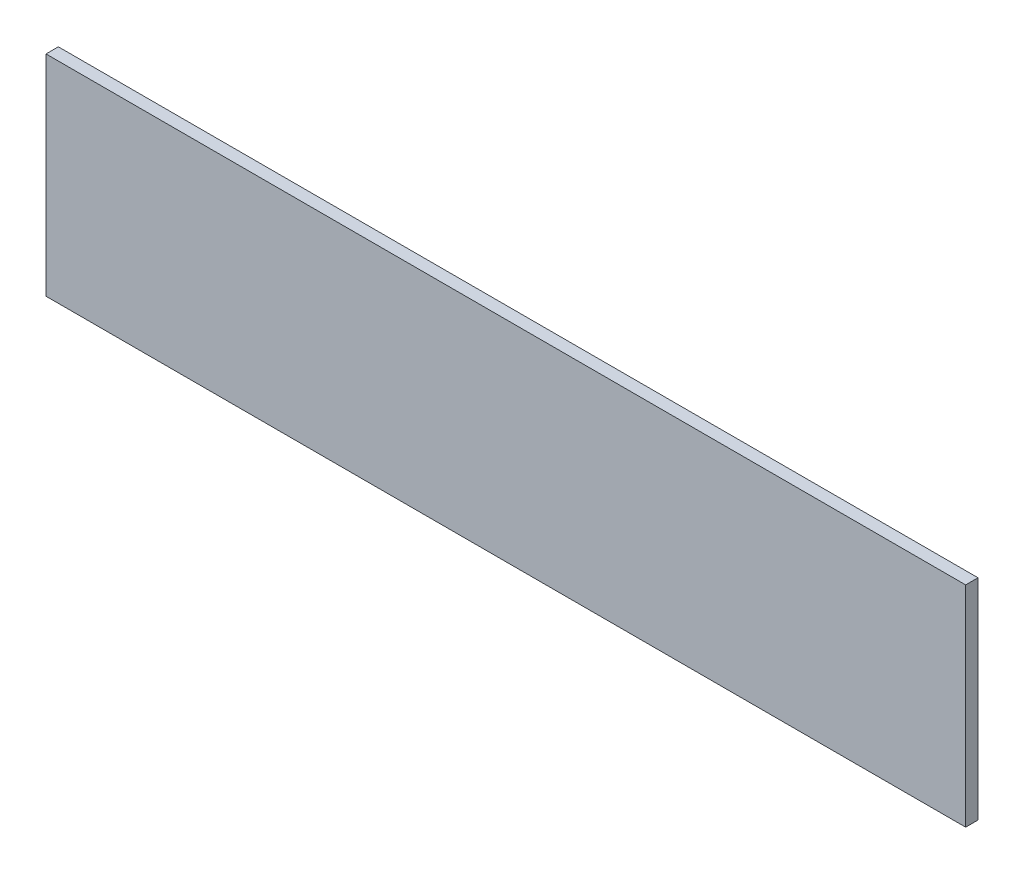
SolidWorks part; units mm, degrees
ref_plane "Front Plane" through (0, 0, 0) normal (0, 0, 1) x (1, 0, 0)
ref_plane "Top Plane" through (0, 0, 0) normal (0, 1, 0) x (1, 0, 0)
ref_plane "Right Plane" through (0, 0, 0) normal (1, 0, 0) x (0, 0, -1)
sketch "Sketch1" plane through (0, 0, 0) normal (0, 0, 1) x (1, 0, 0)
  line L1 (-74.5, -17) -> (74.5, -17)
  line L2 (-74.5, -17) -> (-74.5, 17)
  line L3 (-74.5, 17) -> (74.5, 17)
  line L4 (74.5, -17) -> (74.5, 17)
  line L5 (-74.5, -17) -> (74.5, 17) construction
  line L6 (-74.5, 17) -> (74.5, -17) construction
  point P0 (0, 0)
  dimension "D1" = 149
  dimension "D2" = 34
extrude "Boss-Extrude1" add sketch "Sketch1" along normal blind 2
